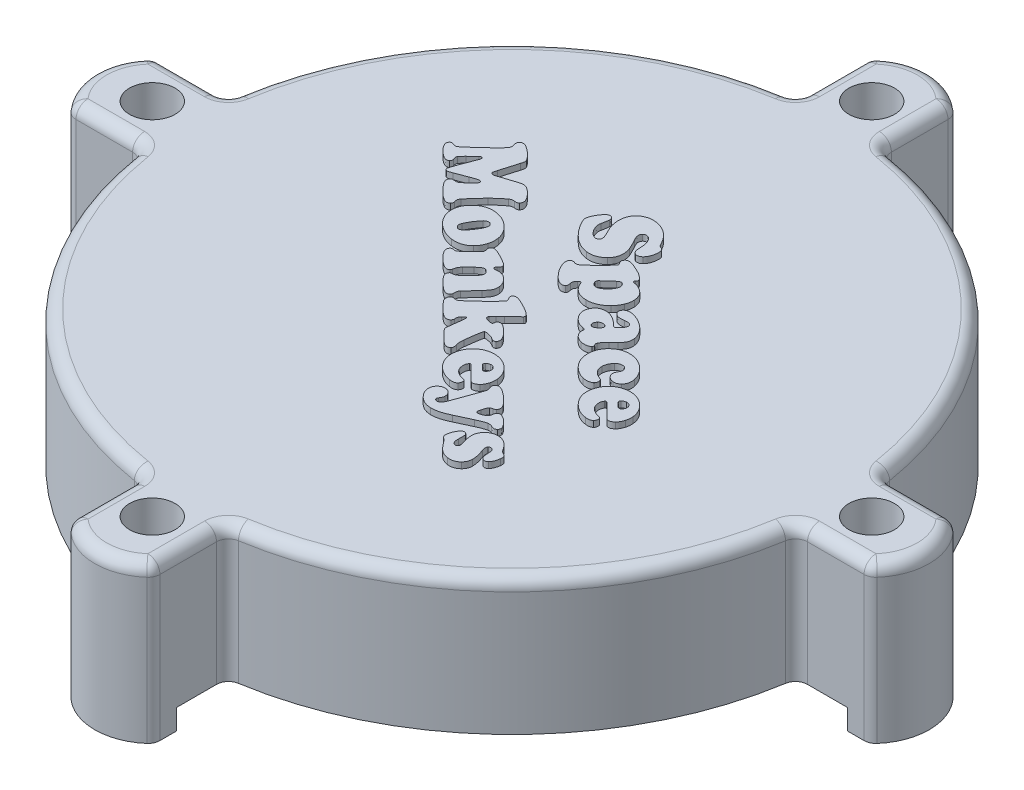
SolidWorks part; units mm, degrees
other "motor_mount" parameters "D1"=97.7653, "D2"=14.7748, "D5"=1.5153, "D6"=1.2729, "D7"=2.6145, "D8"=27.5115, "D9"=27.5368, "D10"=3, "D11"=7.957, "D12"=2, "D14"=6.8142, "D15"=5.6048, "D3"=4.7737, "D4"=4.1559, "D13"=13.0555
ref_plane "Front Plane" through (0, 0, 0) normal (0, 0, 1) x (1, 0, 0)
ref_plane "Top Plane" through (0, 0, 0) normal (0, 1, 0) x (1, 0, 0)
ref_plane "Right Plane" through (0, 0, 0) normal (1, 0, 0) x (0, 0, -1)
sketch "Sketch1" plane through (0, 0, 0) normal (0, 1, 0) x (1, 0, 0)
  line L0 (33.2848, 3.5) -> (27.2764, 3.5)
  line L1 (33.2848, -3.5) -> (27.2764, -3.5)
  line L2 (3.5, -33.2848) -> (3.5, -27.2764)
  line L3 (-3.5, -33.2848) -> (-3.5, -27.2764)
  line L4 (0, 0) -> (30, 0) construction
  line L5 (-33.2848, -3.5) -> (-27.2764, -3.5)
  line L6 (-33.2848, 3.5) -> (-27.2764, 3.5)
  line L7 (-3.5, 33.2848) -> (-3.5, 27.2764)
  line L8 (3.5, 33.2848) -> (3.5, 27.2764)
  line L9 (0, 0) -> (27.2764, -3.5) construction
  line L10 (0, 0) -> (-3.5, -27.2764) construction
  circle A0 centre (0, 0) radius 27.5 construction
  circle A8 centre (30, 0) radius 1.9
  circle A12 centre (0, 0) radius 27.5
  arc A14 (3.5, -33.2848) -> (-3.5, -33.2848) centre (0, -30) cw
  circle A16 centre (0, -30) radius 1.9
  arc A18 (-33.2848, -3.5) -> (-33.2848, 3.5) centre (-30, 0) cw
  arc A19 (33.2848, 3.5) -> (33.2848, -3.5) centre (30, 0) cw
  circle A20 centre (-30, 0) radius 1.9
  arc A21 (-3.5, 33.2848) -> (3.5, 33.2848) centre (0, 30) cw
  circle A22 centre (0, 30) radius 1.9
  dimension "D1" = 55
  dimension "D12" = 3.8
  dimension "D3" = 4.8
  dimension "D13" = 30
  dimension "D2" = 7
  dimension "D5" = 90
  dimension "D6" = 27.5
  dimension "D7" = 7.312
  dimension "D4" = 4
extrude "Boss-Extrude2" add sketch "Sketch1" along normal blind 13
sketch "Sketch2" plane through (0, 0, 0) normal (0, -1, 0) x (1, 0, 0)
  line L0 (-1.9134, 32.6271) -> (-16.1899, 22.2292)
  line L1 (1.9134, 32.6271) -> (16.1899, 22.2292)
  line L9 (32.6271, -1.9134) -> (22.2292, -16.1899)
  line L10 (32.6271, 1.9134) -> (22.2292, 16.1899)
  line L12 (-1.9134, -32.6271) -> (-16.1899, -22.2292)
  line L13 (1.9134, -32.6271) -> (16.1899, -22.2292)
  line L15 (-32.6271, 1.9134) -> (-22.2292, 16.1899)
  line L24 (-32.6271, -1.9134) -> (-22.2292, -16.1899)
  line L25 (0, 0) -> (16.1899, 22.2292) construction
  arc A0 (-1.9134, 32.6271) -> (1.9134, 32.6271) centre (0, 30) cw
  circle A1 centre (0, 30) radius 1.9 construction
  circle A2 centre (0, 30) radius 1.9
  arc A25 (-16.1899, 22.2292) -> (-22.2292, 16.1899) centre (0, 0) ccw
  circle A26 centre (30, 0) radius 1.9
  arc A27 (32.6271, 1.9134) -> (32.6271, -1.9134) centre (30, 0) cw
  circle A28 centre (0, -30) radius 1.9
  arc A29 (1.9134, -32.6271) -> (-1.9134, -32.6271) centre (0, -30) cw
  circle A30 centre (-30, 0) radius 1.9
  arc A31 (-32.6271, -1.9134) -> (-32.6271, 1.9134) centre (-30, 0) cw
  arc A32 (22.2292, 16.1899) -> (16.1899, 22.2292) centre (0, 0) ccw
  arc A33 (16.1899, -22.2292) -> (22.2292, -16.1899) centre (0, 0) ccw
  arc A34 (-22.2292, -16.1899) -> (-16.1899, -22.2292) centre (0, 0) ccw
  dimension "D1" = 55
  dimension "D5" = 16.1899
  dimension "D3" = 4
extrude "Cut-Extrude1" cut sketch "Sketch2" against normal blind 1.7
sketch "Sketch3" plane through (0, 1.7, 0) normal (0, -1, 0) x (1, 0, 0)
  circle A0 centre (0, 0) radius 25.75
  dimension "D1" = 51.5
extrude "Cut-Extrude2" cut sketch "Sketch3" against normal blind 10
fillet "Fillet1" radius 1 32 edges at (27.2764, 7.35, 3.5) (3.5, 7.35, 27.2764) (3.5, 6.5, 33.2848) (-3.5, 6.5, 33.2848) (-3.5, 7.35, 27.2764) (-27.2764, 7.35, 3.5) (-33.2848, 6.5, 3.5) (-27.2764, 7.35, -3.5) (-33.2848, 6.5, -3.5) (-3.5, 6.5, -33.2848) (-3.5, 7.35, -27.2764) (3.5, 7.35, -27.2764) (3.5, 6.5, -33.2848) (33.2848, 6.5, 3.5) (33.2848, 6.5, -3.5) (27.2764, 7.35, -3.5) (30.2806, 13, -3.5) (34.8, 13, 0) (30.2806, 13, 3.5) (19.4454, 13, 19.4454) (3.5, 13, 30.2806) (0, 13, 34.8) (-3.5, 13, 30.2806) (-19.4454, 13, 19.4454) (-30.2806, 13, 3.5) (-34.8, 13, 0) (-30.2806, 13, -3.5) (-19.4454, 13, -19.4454) (-3.5, 13, -30.2806) (0, 13, -34.8) (3.5, 13, -30.2806) (19.4454, 13, -19.4454)
sketch "Sketch4" plane through (0, 13, 0) normal (0, 1, 0) x (1, 0, 0)
  line L0 (-3.5839, 9.2408) -> (9.2408, -3.5839) construction
  line L1 (-20.7122, 15.0553) -> (15.0553, -20.7122) construction
  line L2 (0, 0) -> (13.7522, 0) construction
  line L3 (-2.8284, -2.8284) -> (2.8284, 2.8284) construction
  text T0 "Space" font "Cooper Black" height 5
  text T1 "Monkeys" font "Cooper Black" height 5
  point P3 (2.8284, 2.8284)
  point P6 (-2.8284, -2.8284)
  point P11 (0, 0)
  dimension "D1" = 8
  dimension "D2" = 135
extrude "Boss-Extrude3" add sketch "Sketch4" along normal blind 0.5 separate body
equation "\"Hwidth\"= 30"
equation "\"D13@Sketch1\"=\"Hwidth\""
equation "\"Mdia\"=2.3"
equation "\"Shaft\"=8.3"
equation "\"Mounthole\"=3.8"
equation "\"D12@Sketch1\"=\"Mounthole\""
equation "\"MainDia\"=55"
equation "\"D1@Sketch1\"=\"MainDia\""
